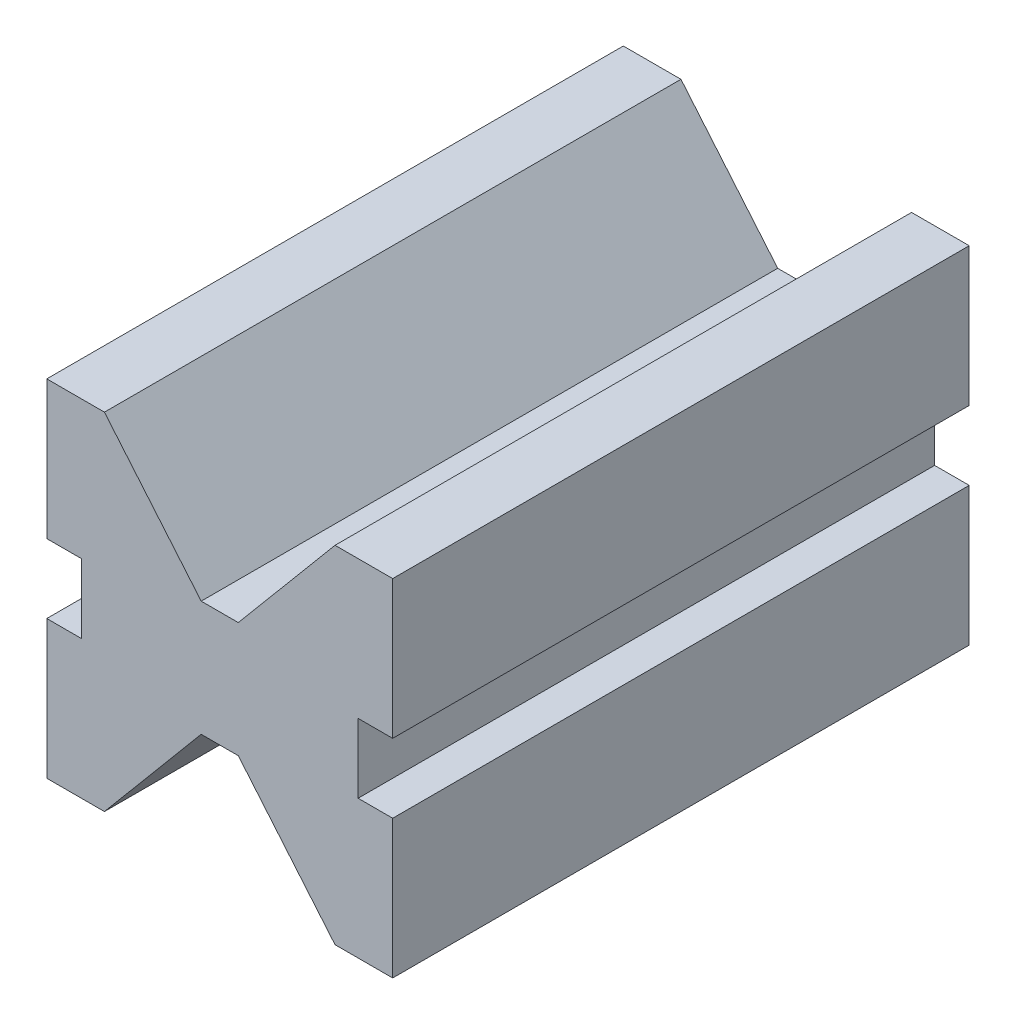
SolidWorks part; units mm, degrees
material "1060 Alloy"
ref_plane "Front Plane" through (0, 0, 0) normal (0, 0, 1) x (1, 0, 0)
ref_plane "Top Plane" through (0, 0, 0) normal (0, 1, 0) x (1, 0, 0)
ref_plane "Right Plane" through (0, 0, 0) normal (1, 0, 0) x (0, 0, -1)
sketch "Sketch1" plane through (0, 0, 0) normal (0, 0, 1) x (1, 0, 0)
  line L20 (0, 0) -> (-20, 0) construction
  line L21 (-20, 0) -> (-30, 0)
  line L22 (-30, 0) -> (-30, 24)
  line L23 (-30, 24) -> (-24, 24)
  line L24 (-24, 24) -> (-24, 36)
  line L25 (-24, 36) -> (-30, 36)
  line L26 (-30, 36) -> (-30, 60)
  line L27 (-30, 60) -> (-20, 60)
  line L28 (-20, 60) -> (-3.218, 40)
  line L29 (-3.218, 40) -> (3.218, 40)
  line L30 (-20, 0) -> (-3.218, 20)
  line L31 (-3.218, 20) -> (3.218, 20)
  line L32 (0, 0) -> (0, 64.0894) construction
  line L33 (20, 0) -> (3.218, 20)
  line L34 (20, 0) -> (30, 0)
  line L35 (30, 0) -> (30, 24)
  line L36 (30, 24) -> (24, 24)
  line L37 (24, 24) -> (24, 36)
  line L38 (24, 36) -> (30, 36)
  line L39 (30, 36) -> (30, 60)
  line L40 (30, 60) -> (20, 60)
  line L41 (20, 60) -> (3.218, 40)
  line L42 (-20, 60) -> (20, 60) construction
  point P3 (30, 0)
  point P15 (0, 20)
  point P26 (30, 20)
  point P27 (0, 40)
  dimension "D1" = 10
  dimension "D2" = 12
  dimension "D3" = 60
  dimension "D4" = 6
  dimension "D5" = 24
  dimension "D6" = 20
  dimension "D7" = 50
  dimension "D8" = 20
  dimension "D9" = 50
  dimension "D10" = 60
  dimension "D11" = 60
  dimension "D12" = 40
extrude "Boss-Extrude1" add sketch "Sketch1" against normal blind 100
